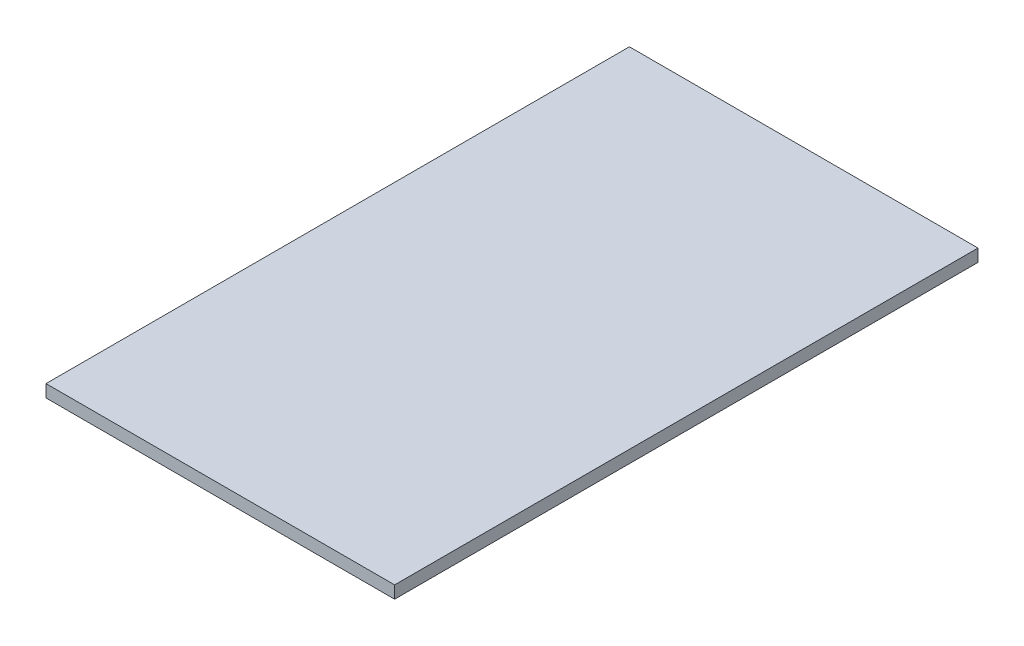
SolidWorks part; units mm, degrees
ref_plane "Front Plane" through (0, 0, 0) normal (0, 0, 1) x (1, 0, 0)
ref_plane "Top Plane" through (0, 0, 0) normal (0, 1, 0) x (1, 0, 0)
ref_plane "Right Plane" through (0, 0, 0) normal (1, 0, 0) x (0, 0, -1)
sketch "Sketch1" plane through (0, 0, 0) normal (0, 1, 0) x (1, 0, 0)
  line L1 (-49, -82) -> (49, -82)
  line L2 (-49, -82) -> (-49, 82)
  line L3 (-49, 82) -> (49, 82)
  line L4 (49, -82) -> (49, 82)
  line L5 (-49, -82) -> (49, 82) construction
  line L6 (-49, 82) -> (49, -82) construction
  point P0 (0, 0)
  dimension "D1" = 164
  dimension "D2" = 98
extrude "MAIN BODY" add sketch "Sketch1" along normal blind 3.5
sketch "Sketch2" plane through (0, 0, 0) normal (0, -1, 0) x (1, 0, 0)
  line L0 (49, -82) -> (-49, -82) construction
  line L1 (-49, -82) -> (25, -82)
  line L2 (-49, -82) -> (-49, -42)
  line L3 (-49, -42) -> (25, -42)
  line L4 (25, -82) -> (25, -42)
  line L5 (-49, -82) -> (-49, 82) construction
  line L6 (49, 82) -> (49, -82) construction
  dimension "D1" = 0
  dimension "D2" = 24
  dimension "D3" = 40
extrude "PCBs AND SUCH" add sketch "Sketch2" along normal blind 5
